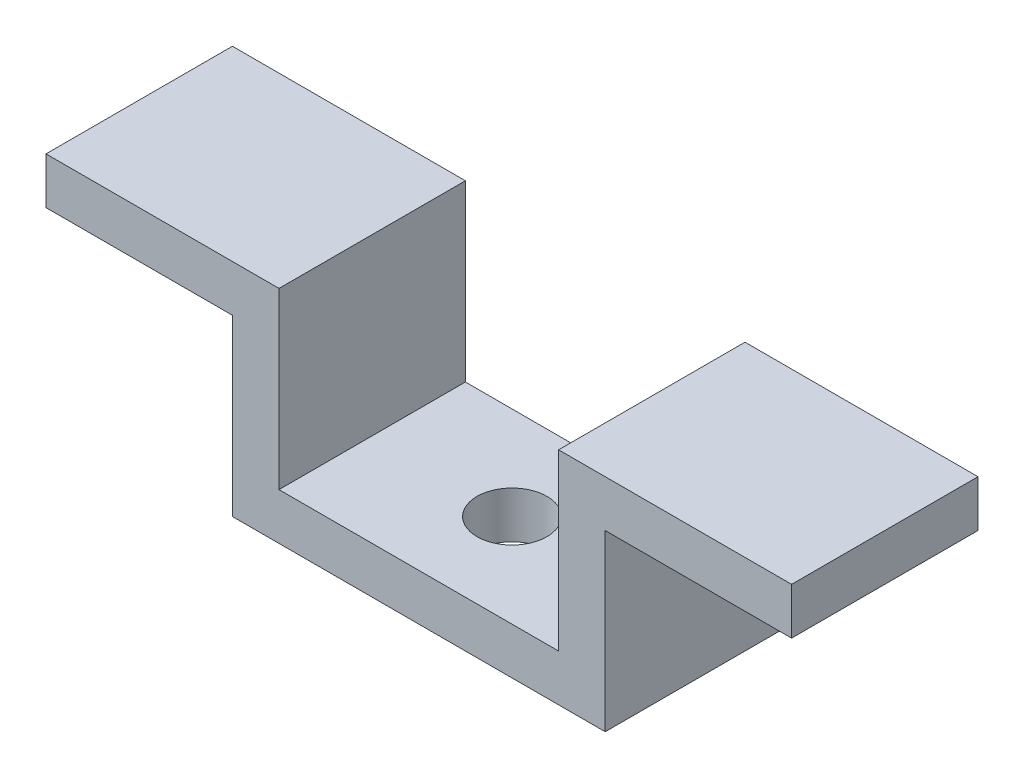
SolidWorks part; units mm, degrees
ref_plane "Front Plane" through (0, 0, 0) normal (0, 0, 1) x (1, 0, 0)
ref_plane "Top Plane" through (0, 0, 0) normal (0, 1, 0) x (1, 0, 0)
ref_plane "Right Plane" through (0, 0, 0) normal (1, 0, 0) x (0, 0, -1)
sketch "Sketch1" plane through (0, 0, 0) normal (0, 0, 1) x (1, 0, 0)
  line L0 (0, 0) -> (25.4, 0)
  line L1 (25.4, 0) -> (25.4, 23.749)
  line L2 (25.4, 23.749) -> (50.8, 23.749)
  line L3 (50.8, 23.749) -> (50.8, 30.099)
  line L4 (50.8, 30.099) -> (19.05, 30.099)
  line L5 (19.05, 30.099) -> (19.05, 6.35)
  line L6 (19.05, 6.35) -> (0, 6.35)
  line L7 (0, 6.35) -> (0, 0)
  dimension "D1" = 25.4
  dimension "D2" = 6.35
  dimension "D3" = 6.35
  dimension "D4" = 6.35
  dimension "D5" = 50.8
  dimension "D6" = 23.749
extrude "Boss-Extrude1" add sketch "Sketch1" along normal blind 25.4
mirror "Mirror1" about plane through (0, 6.35, 25.4) normal (1, 0, 0) of bodies 101
sketch "Sketch2" plane through (0, 6.35, 0) normal (0, 1, 0) x (1, 0, 0)
  line L0 (0, -25.4) -> (0, -12.7) construction
  line L1 (19.05, -25.4) -> (-19.05, -25.4) construction
  line L2 (0, -12.7) -> (0, 0) construction
  circle A0 centre (0, -12.7) radius 4.7625
  dimension "D1" = 9.525
extrude "Cut-Extrude1" cut sketch "Sketch2" against normal up to next
